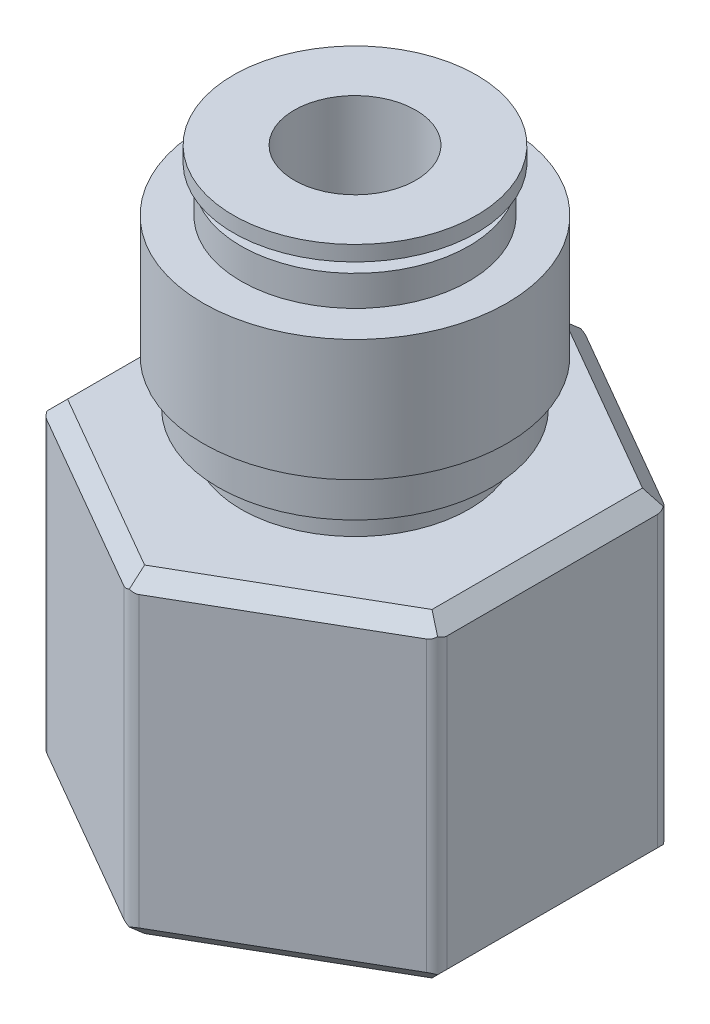
SolidWorks part; units mm, degrees
ref_plane "Спереди" through (0, 0, 0) normal (0, 0, 1) x (1, 0, 0)
ref_plane "Сверху" through (0, 0, 0) normal (0, 1, 0) x (1, 0, 0)
ref_plane "Справа" through (0, 0, 0) normal (1, 0, 0) x (0, 0, -1)
sketch "Эскиз1" plane through (0, 0, 0) normal (0, 1, 0) x (1, 0, 0)
  line L1 (0, 15) -> (-12.9904, 7.5)
  line L2 (-12.9904, 7.5) -> (-12.9904, -7.5)
  line L3 (-12.9904, -7.5) -> (0, -15)
  line L4 (0, -15) -> (12.9904, -7.5)
  line L5 (12.9904, -7.5) -> (12.9904, 7.5)
  line L6 (12.9904, 7.5) -> (0, 15)
  circle A0 centre (0, 0) radius 12.9904 construction
  circle A1 centre (0, 0) radius 15 construction
  dimension "D1" = 30
extrude "Бобышка-Вытянуть1" add sketch "Эскиз1" along normal blind 21
sketch "Эскиз2" plane through (0, 21, 0) normal (0, 1, 0) x (1, 0, 0)
  circle A0 centre (0, 0) radius 7.5
  dimension "D1" = 15
extrude "Бобышка-Вытянуть2" add sketch "Эскиз2" along normal blind 2
sketch "Эскиз3" plane through (0, 23, 0) normal (0, 1, 0) x (1, 0, 0)
  circle A0 centre (0, 0) radius 9
  dimension "D1" = 18
extrude "Бобышка-Вытянуть3" add sketch "Эскиз3" along normal blind 3
sketch "Эскиз4" plane through (0, 26, 0) normal (0, 1, 0) x (1, 0, 0)
  circle A0 centre (0, 0) radius 10
  dimension "D1" = 20
extrude "Бобышка-Вытянуть4" add sketch "Эскиз4" along normal blind 8
sketch "Эскиз5" plane through (0, 34, 0) normal (0, 1, 0) x (1, 0, 0)
  circle A0 centre (0, 0) radius 7.5
  dimension "D1" = 15
extrude "Бобышка-Вытянуть5" add sketch "Эскиз5" along normal blind 2
sketch "Эскиз6" plane through (0, 0, 0) normal (0, 0, 1) x (1, 0, 0)
  line L0 (-8, 37) -> (-6, 37)
  line L1 (-4, 38) -> (-8, 38)
  line L2 (-8, 38) -> (-8, 37)
  line L9 (-4, 38) -> (-4, 36)
  line L10 (-6, 37) -> (-6, 36)
  line L11 (0, 36) -> (0, 38.2854) construction
  line L13 (7.5, 36) -> (-7.5, 36) construction
  line L14 (-6, 36) -> (-4, 36)
revolve "Повернуть1" add sketch "Эскиз6" angle 360 about L11
sketch "Эскиз7" plane through (0, 36, 0) normal (0, 1, 0) x (1, 0, 0)
  circle A0 centre (0, 0) radius 4
extrude "Вырез-Вытянуть1" cut sketch "Эскиз7" against normal through all and the other way through all
hole_wizard "Отверстие обработанное метчиком G1/21" positions "Эскиз8" profile "Эскиз9" tap size "G1/2" standard "ISO"
sketch "Эскиз8" plane through (0, 0, 0) normal (0, -1, 0) x (-1, 0, 0)
  point P0 (0, 0)
sketch "Эскиз9" plane through (0, 0, 0) normal (1, 0, 0) x (0, 0, -1)
  line L0 (0, 0) -> (0, 23.7082)
  line L1 (0, 23.7082) -> (9.5, 18)
  line L2 (9.5, 18) -> (9.5, 0)
  line L5 (9.5, 0) -> (0, 0)
  line L10 (0, 23.7082) -> (-9.5, 18) construction
  line L11 (0, -6.35) -> (0, 107.95) construction
  dimension "Диаметр сверла" = 19
  dimension "Глубина сверла" = 18
  dimension "Угол заточки сверла" = 118
cosmetic thread "Отверстие резьбы1" parameters "D1"=18, "D2"=20.955
chamfer "Фаска1" distance 1 angle 45 13 edges at (12.9904, 21, 0) (6.4952, 21, 11.25) (-6.4952, 21, 11.25) (-12.9904, 21, 0) (-6.4952, 21, -11.25) (6.4952, 21, -11.25) (0, 0, -9.5) (-6.4952, 0, -11.25) (-12.9904, 0, 0) (-6.4952, 0, 11.25) (6.4952, 0, 11.25) (12.9904, 0, 0) (6.4952, 0, -11.25)
fillet "Скругление1" radius 1 6 edges at (12.9904, 10.5, 7.5) (0, 10.5, 15) (-12.9904, 10.5, 7.5) (-12.9904, 10.5, -7.5) (0, 10.5, -15) (12.9904, 10.5, -7.5)
